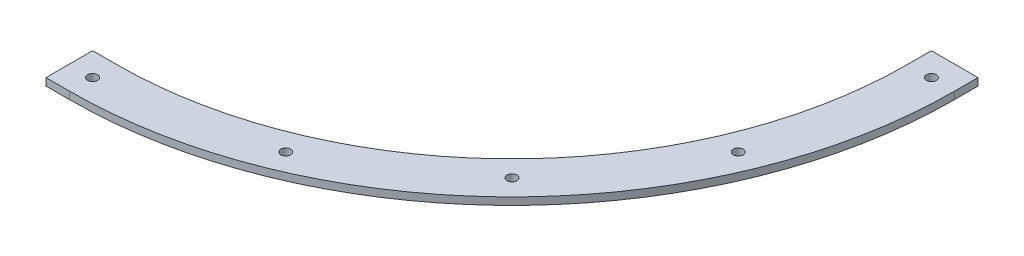
SolidWorks part; units mm, degrees
ref_plane "Front Plane" through (0, 0, 0) normal (0, 0, 1) x (1, 0, 0)
ref_plane "Top Plane" through (0, 0, 0) normal (0, 1, 0) x (1, 0, 0)
ref_plane "Right Plane" through (0, 0, 0) normal (1, 0, 0) x (0, 0, -1)
sketch "Sketch1" plane through (0, 0, 0) normal (0, 1, 0) x (1, 0, 0)
  line L0 (0, -280) -> (100, -280)
  line L1 (100, -280) -> (100, -209.6016)
  line L2 (280, -100) -> (209.6016, -100)
  line L3 (0, 0) -> (0, -280) construction
  line L4 (280, 0) -> (280, -100)
  line L5 (-280, 280) -> (280, 280) construction
  line L6 (-280, 280) -> (-280, -280) construction
  line L7 (-280, -280) -> (280, -280) construction
  line L8 (280, 280) -> (280, -280) construction
  line L9 (-280, 280) -> (280, -280) construction
  line L10 (-280, -280) -> (280, 280) construction
  line L11 (100, -209.6016) -> (209.6016, -100)
  line L12 (-280, 0) -> (-280, -100)
  line L13 (-280, -100) -> (-209.6016, -100)
  line L14 (-209.6016, -100) -> (-100, -209.6016)
  line L15 (-100, -280) -> (-100, -209.6016)
  line L16 (0, -280) -> (-100, -280)
  line L17 (0, 280) -> (-100, 280)
  line L18 (-100, 280) -> (-100, 209.6016)
  line L19 (-100, 209.6016) -> (-209.6016, 100)
  line L20 (-280, 100) -> (-209.6016, 100)
  line L21 (-280, 0) -> (-280, 100)
  line L22 (280, 0) -> (280, 100)
  line L23 (280, 100) -> (209.6016, 100)
  line L24 (209.6016, 100) -> (100, 209.6016)
  line L25 (100, 280) -> (100, 209.6016)
  line L26 (0, 280) -> (100, 280)
  line L27 (111.5258, -219.2889) -> (219.2889, -111.5258) construction
  line L28 (219.2889, -111.5258) -> (247.5732, -139.8101) construction
  line L29 (247.5732, -139.8101) -> (139.8101, -247.5732) construction
  line L30 (139.8101, -247.5732) -> (111.5258, -219.2889) construction
  line L31 (-100, -270) -> (100, -270) construction
  line L32 (-90, -280) -> (-90, 280) construction
  line L33 (-75, -75) -> (75, -75) construction
  line L34 (-75, -75) -> (-75, 75) construction
  line L35 (-75, 75) -> (75, 75) construction
  line L36 (75, -75) -> (75, 75) construction
  line L37 (-75, -75) -> (75, 75) construction
  line L38 (-75, 75) -> (75, -75) construction
  line L39 (-100, -260) -> (100, -260) construction
  line L40 (-280, 40) -> (280, 40) construction
  line L41 (0, 280) -> (0, 0) construction
  line L42 (-280, -90) -> (280, -90) construction
  line L43 (-260, -100) -> (-260, 100) construction
  line L44 (0, 0) -> (-280, 0) construction
  arc A0 (100, -280) -> (280, -100) centre (100, -100) ccw construction
  circle A1 centre (-47.5, -192) radius 2.125
  circle A2 centre (-47.5, -217) radius 2.125
  circle A3 centre (47.5, -217) radius 2.125
  circle A4 centre (47.5, -192) radius 2.125
  circle A5 centre (-192, 47.5) radius 2.125
  circle A6 centre (-217, 47.5) radius 2.125
  circle A7 centre (-192, -47.5) radius 2.125
  circle A8 centre (-217, -47.5) radius 2.125
  circle A9 centre (47.5, 192) radius 2.125
  circle A10 centre (47.5, 217) radius 2.125
  circle A11 centre (-47.5, 192) radius 2.125
  circle A12 centre (-47.5, 217) radius 2.125
  circle A13 centre (192, -47.5) radius 2.125
  circle A14 centre (217, -47.5) radius 2.125
  circle A15 centre (192, 47.5) radius 2.125
  circle A16 centre (217, 47.5) radius 2.125
  circle A17 centre (-90, -270) radius 2.125
  circle A18 centre (-30, -270) radius 2.125
  circle A19 centre (30, -270) radius 2.125
  circle A20 centre (90, -270) radius 2.125
  circle A21 centre (-270, 90) radius 2.125
  circle A22 centre (-270, 30) radius 2.125
  circle A23 centre (-270, -30) radius 2.125
  circle A24 centre (-270, -90) radius 2.125
  circle A25 centre (90, 270) radius 2.125
  circle A26 centre (30, 270) radius 2.125
  circle A27 centre (-30, 270) radius 2.125
  circle A28 centre (-90, 270) radius 2.125
  circle A29 centre (270, -90) radius 2.125
  circle A30 centre (270, -30) radius 2.125
  circle A31 centre (270, 30) radius 2.125
  circle A32 centre (270, 90) radius 2.125
  circle A33 centre (-90, -250) radius 2.125
  circle A34 centre (-90, -180) radius 2.125
  circle A35 centre (-90, -110) radius 2.125
  circle A36 centre (-90, -40) radius 2.125
  circle A37 centre (-90, 30) radius 2.125
  circle A38 centre (-90, 50) radius 2.125
  circle A39 centre (-90, 100) radius 2.125 construction
  circle A40 centre (-90, 150) radius 2.125
  circle A41 centre (-90, 200) radius 2.125 construction
  circle A42 centre (-90, 250) radius 2.125
  circle A43 centre (90, -250) radius 2.125
  circle A44 centre (90, -180) radius 2.125
  circle A45 centre (90, -110) radius 2.125
  circle A46 centre (90, -40) radius 2.125
  circle A47 centre (90, 30) radius 2.125
  circle A48 centre (90, 50) radius 2.125
  circle A49 centre (90, 100) radius 2.125 construction
  circle A50 centre (90, 150) radius 2.125
  circle A51 centre (90, 200) radius 2.125 construction
  circle A52 centre (90, 250) radius 2.125
  circle A53 centre (-250, -90) radius 2.125
  circle A54 centre (-180, -90) radius 2.125
  circle A55 centre (-110, -90) radius 2.125
  circle A56 centre (-110, 90) radius 2.125
  circle A57 centre (-180, 90) radius 2.125
  circle A58 centre (-250, 90) radius 2.125
  circle A59 centre (110, -90) radius 2.125
  circle A60 centre (180, -90) radius 2.125
  circle A61 centre (250, -90) radius 2.125
  circle A62 centre (110, 90) radius 2.125
  circle A63 centre (180, 90) radius 2.125
  circle A64 centre (250, 90) radius 2.125
  point P33 (0, 0)
  point P68 (0, 0)
  point P107 (0, 0)
  dimension "D10" = 25
  dimension "4.25" = 4.25
  dimension "D11" = 4.25
  dimension "D16" = 4.25
  dimension "D24" = 4.25
  dimension "D28" = 4.25
  dimension "D32" = 4.25
  dimension "D1" = 560
  dimension "D2" = 90
  dimension "D3" = 280
  dimension "D4" = 4
  dimension "D5" = 100
  dimension "D6" = 155
  dimension "D7" = 152.4
  dimension "D8" = 15
  dimension "D9" = 40
  dimension "D12" = 47.5
  dimension "D13" = 63
  dimension "D15" = 10
  dimension "D17" = 10
  dimension "D18" = 76.2
  dimension "D19" = 150
  dimension "D20" = 150
  dimension "D23" = 10
  dimension "D25" = 10
  dimension "D26" = 300
  dimension "D29" = 10
  dimension "D31" = 20
  dimension "D33" = 10
  dimension "D21" = 4
  dimension "D27" = 5
  dimension "D30" = 5
  dimension "D34" = 3
  dimension "D14" = 4
  dimension "D22" = 4
extrude "Boss-Extrude1" add sketch "Sketch1" along normal blind 3.175 contours L26 L17 L18 L19 L20 L21 L12 L13 L14 L15 L16 L0 L1 L11 L2 L4 L22 L23 L24 L25
sketch "Sketch2" plane through (0, 3.175, 0) normal (0, 1, 0) x (1, 0, 0)
  line L11 (80, -260) -> (100, -260)
  line L12 (80, -260) -> (80, -280)
  line L13 (80, -280) -> (93.1985, -280) construction
  line L14 (100, -260) -> (100, -280) construction
  line L15 (80, -260) -> (100, -280) construction
  line L16 (80, -280) -> (100, -260) construction
  line L17 (260, -80) -> (280, -80)
  line L18 (260, -80) -> (260, -100)
  line L19 (260, -100) -> (280, -100) construction
  line L20 (280, -80) -> (280, -100) construction
  line L21 (260, -80) -> (280, -100) construction
  line L22 (260, -100) -> (280, -80) construction
  line L38 (100, 280) -> (-100, 280)
  line L39 (-100, 280) -> (-100, 209.6016)
  line L40 (-100, 209.6016) -> (-209.6016, 100)
  line L41 (-209.6016, 100) -> (-280, 100)
  line L42 (-280, 100) -> (-280, -100)
  line L43 (-280, -100) -> (-209.6016, -100)
  line L44 (-209.6016, -100) -> (-100, -209.6016)
  line L45 (-100, -209.6016) -> (-100, -280)
  line L46 (-100, -280) -> (100, -280)
  line L47 (100, -280) -> (100, -209.6016)
  line L48 (100, -209.6016) -> (209.6016, -100)
  line L49 (209.6016, -100) -> (280, -100)
  line L50 (280, -100) -> (280, 100)
  line L51 (280, 100) -> (209.6016, 100)
  line L52 (209.6016, 100) -> (100, 209.6016)
  line L53 (100, 209.6016) -> (100, 280)
  line L54 (100, 280) -> (-100, 280)
  line L55 (-100, 280) -> (-100, 209.6016)
  line L56 (-100, 209.6016) -> (-209.6016, 100)
  line L57 (-209.6016, 100) -> (-280, 100)
  line L58 (-280, 100) -> (-280, -100)
  line L59 (-280, -100) -> (-209.6016, -100)
  line L60 (-209.6016, -100) -> (-100, -209.6016)
  line L61 (-100, -209.6016) -> (-100, -280)
  line L62 (-100, -280) -> (80, -280)
  line L63 (100, -260) -> (100, -209.6016)
  line L64 (100, -209.6016) -> (209.6016, -100)
  line L65 (209.6016, -100) -> (260, -100)
  line L66 (280, -80) -> (280, 100)
  line L67 (280, 100) -> (209.6016, 100)
  line L68 (209.6016, 100) -> (100, 209.6016)
  line L69 (100, 209.6016) -> (100, 280)
  point P0 (90, -270)
  point P5 (270, -90)
  dimension "D1" = 0
extrude "Cut-Extrude1" cut sketch "Sketch2" against normal through all
sketch "Sketch3" plane through (0, 3.175, 0) normal (0, 1, 0) x (1, 0, 0)
  line L0 (260, -90) -> (267.875, -90)
  line L1 (272.125, -90) -> (280, -90)
  line L2 (90, -260) -> (90, -267.875)
  line L3 (90, -280) -> (90, -272.125)
  arc A0 (90, -270) -> (270, -90) centre (90, -90) ccw construction
  arc A1 (90, -280) -> (280, -90) centre (90, -90) ccw
  arc A2 (90, -260) -> (260, -90) centre (90, -90) ccw
  circle A3 centre (270, -90) radius 2.125 construction
  circle A4 centre (90, -270) radius 2.125 construction
  arc A5 (267.875, -90) -> (272.125, -90) centre (270, -90) ccw
  arc A6 (90, -272.125) -> (90, -267.875) centre (90, -270) ccw
  dimension "D1" = 10
  dimension "D2" = 10
extrude "Boss-Extrude2" add sketch "Sketch3" against normal up to surface (3.175 mm away) up to face at (90, 0, 272.125)
sketch "Sketch4" plane through (0, 3.175, 0) normal (0, 1, 0) x (1, 0, 0)
  line L0 (90, -90) -> (217.2792, -217.2792) construction
  line L1 (100, -280) -> (100, -279.7367) construction
  line L2 (100, -280) -> (80, -280) construction
  line L3 (100, -280) -> (90, -280)
  line L4 (100, -280) -> (100, -279.7367)
  line L7 (279.7367, -100) -> (284.4157, -100)
  line L8 (284.4157, -100) -> (280, -90)
  arc A0 (90, -270) -> (270, -90) centre (90, -90) ccw construction
  arc A1 (90, -270) -> (270, -90) centre (90, -90) ccw construction
  circle A2 centre (217.2792, -217.2792) radius 2.125
  circle A3 centre (256.2075, -159.102) radius 2.125
  circle A4 centre (159.102, -256.2075) radius 2.125
  arc A5 (90, -280) -> (280, -90) centre (90, -90) ccw construction
  arc A6 (90, -280) -> (100, -279.7367) centre (90, -90) ccw
  arc A7 (280, -90) -> (279.7367, -100) centre (90, -90) cw
  dimension "D1" = 4.25
  dimension "D2" = 4.25
  dimension "D3" = 70
extrude "Cut-Extrude2" cut sketch "Sketch4" against normal through all
